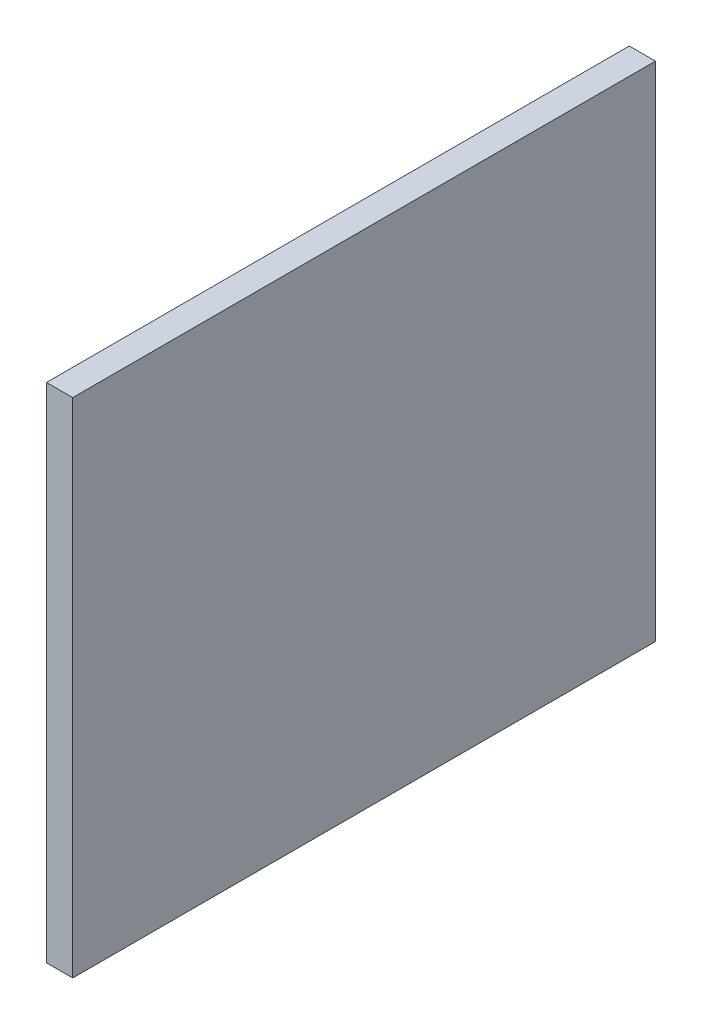
SolidWorks part; units mm, degrees
ref_plane "Front" through (0, 0, 0) normal (0, 0, 1) x (1, 0, 0)
ref_plane "Top" through (0, 0, 0) normal (0, 1, 0) x (1, 0, 0)
ref_plane "Right" through (0, 0, 0) normal (1, 0, 0) x (0, 0, -1)
sketch "Sketch1" plane through (0, 0, 0) normal (1, 0, 0) x (0, 0, -1)
  line L1 (-200, -172.5) -> (200, -172.5)
  line L2 (-200, -172.5) -> (-200, 172.5)
  line L3 (-200, 172.5) -> (200, 172.5)
  line L4 (200, -172.5) -> (200, 172.5)
  line L5 (-200, -172.5) -> (200, 172.5) construction
  line L6 (-200, 172.5) -> (200, -172.5) construction
  point P0 (0, 0)
  dimension "D1" = 400
  dimension "D2" = 345
extrude "Boss-Extrude1" add sketch "Sketch1" along normal blind 18
